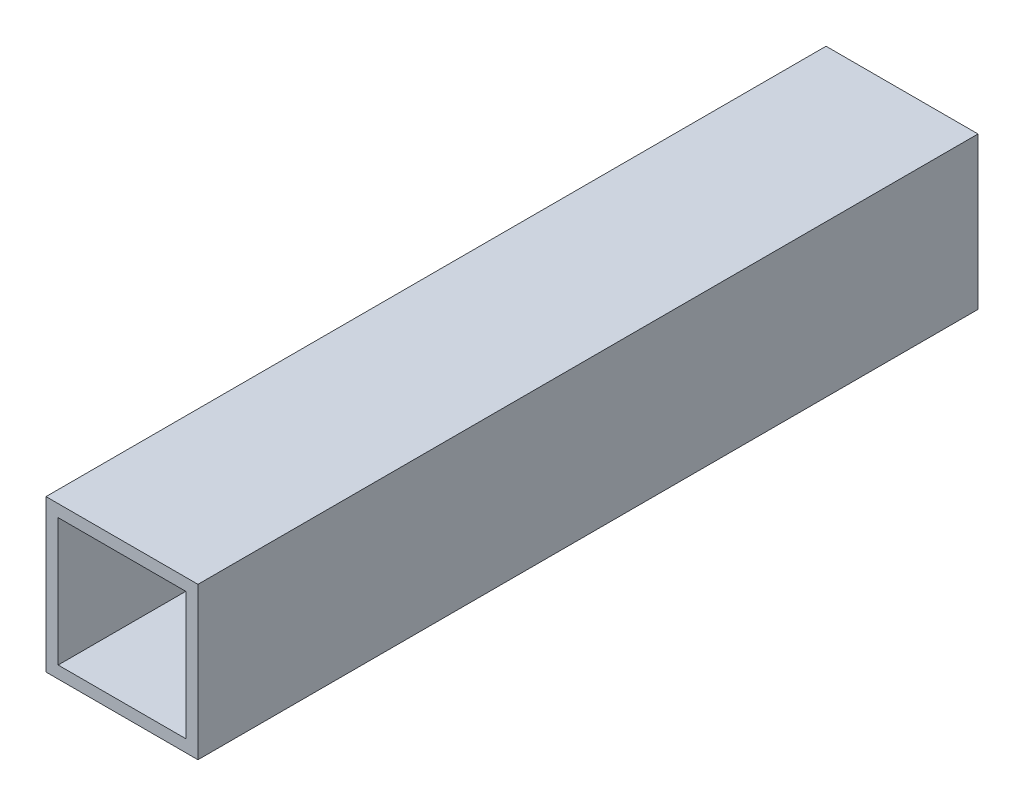
SolidWorks part; units mm, degrees
material "7050-T73510"
ref_plane "Front" through (0, 0, 0) normal (0, 0, 1) x (1, 0, 0)
ref_plane "Top" through (0, 0, 0) normal (0, 1, 0) x (1, 0, 0)
ref_plane "Right" through (0, 0, 0) normal (1, 0, 0) x (0, 0, -1)
sketch "草图1" plane through (0, 0, 0) normal (0, 0, 1) x (1, 0, 0)
  line L0 (-6.3, -6.3) -> (-6.3, 6.3)
  line L1 (-7.5, -7.5) -> (7.5, -7.5)
  line L2 (-7.5, -7.5) -> (-7.5, 7.5)
  line L3 (-7.5, 7.5) -> (7.5, 7.5)
  line L4 (7.5, -7.5) -> (7.5, 7.5)
  line L5 (-7.5, -7.5) -> (7.5, 7.5) construction
  line L6 (-7.5, 7.5) -> (7.5, -7.5) construction
  line L7 (-6.3, 6.3) -> (6.3, 6.3)
  line L8 (6.3, -6.3) -> (6.3, 6.3)
  line L9 (-6.3, -6.3) -> (6.3, -6.3)
  point P0 (0, 0)
  dimension "D1" = 15
  dimension "D2" = 15
  dimension "D3" = 1.2
extrude "凸台-拉伸1" add sketch "草图1" along normal blind 77
